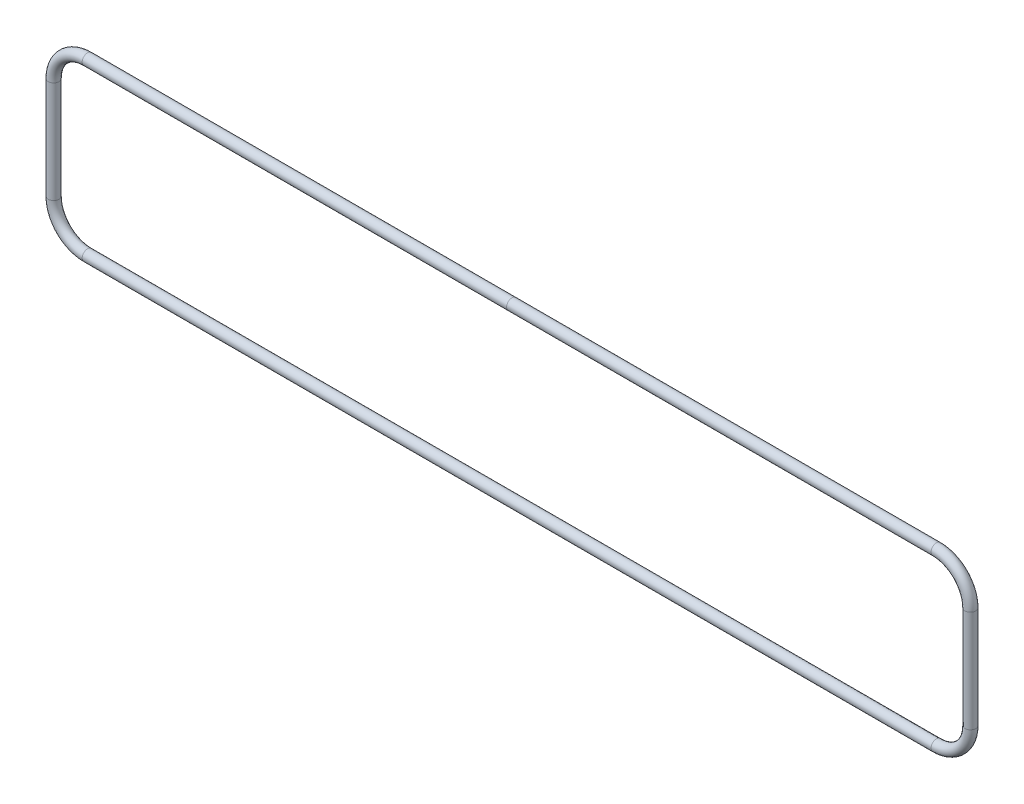
SolidWorks part; units mm, degrees
material "1.0035 (S185)"
ref_plane "Plano frontal" through (0, 0, 0) normal (0, 0, 1) x (1, 0, 0)
ref_plane "Plano superior" through (0, 0, 0) normal (0, 1, 0) x (1, 0, 0)
ref_plane "Plano direito" through (0, 0, 0) normal (1, 0, 0) x (0, 0, -1)
sketch "Esboço1" plane through (0, 0, 0) normal (0, 0, 1) x (1, 0, 0)
  line L1 (-405, 75) -> (405, 75) construction
  line L2 (-405, 75) -> (-405, -75) construction
  line L3 (-405, -75) -> (405, -75) construction
  line L4 (405, 75) -> (405, -75) construction
  line L5 (-405, 75) -> (405, -75) construction
  line L6 (-405, -75) -> (405, 75) construction
  line L7 (375, -75) -> (-375, -75)
  line L8 (405, -45) -> (405, 45)
  line L9 (375, 75) -> (-375, 75)
  line L10 (-405, -45) -> (-405, 45)
  line L11 (405, -75) -> (-405, 75) construction
  line L12 (405, 75) -> (-405, -75) construction
  arc A0 (-405, -45) -> (-375, -75) centre (-375, -45) ccw
  arc A1 (375, -75) -> (405, -45) centre (375, -45) ccw
  arc A2 (405, 45) -> (375, 75) centre (375, 45) ccw
  arc A3 (-375, 75) -> (-405, 45) centre (-375, 45) ccw
  point P0 (0, 0)
  point P6 (0, 0)
  dimension "D3" = 30
  dimension "D1" = 810
  dimension "D2" = 150
sketch "Esboço2" plane through (0, 0, 0) normal (1, 0, 0) x (0, 0, -1)
  circle A0 centre (0, 75) radius 4.7625
  dimension "D1" = 9.525
sweep "Varredura1" add profiles "Esboço2" path "Esboço1"
ref_plane "Plano1" through (0, 0, 10) normal (0, 0, 1) x (1, 0, 0)
ref_plane "Plano2" through (-375, 0, 0) normal (1, 0, 0) x (0, 0, -1)
ref_plane "Plano3" through (375, 0, 0) normal (1, 0, 0) x (0, 0, -1)
